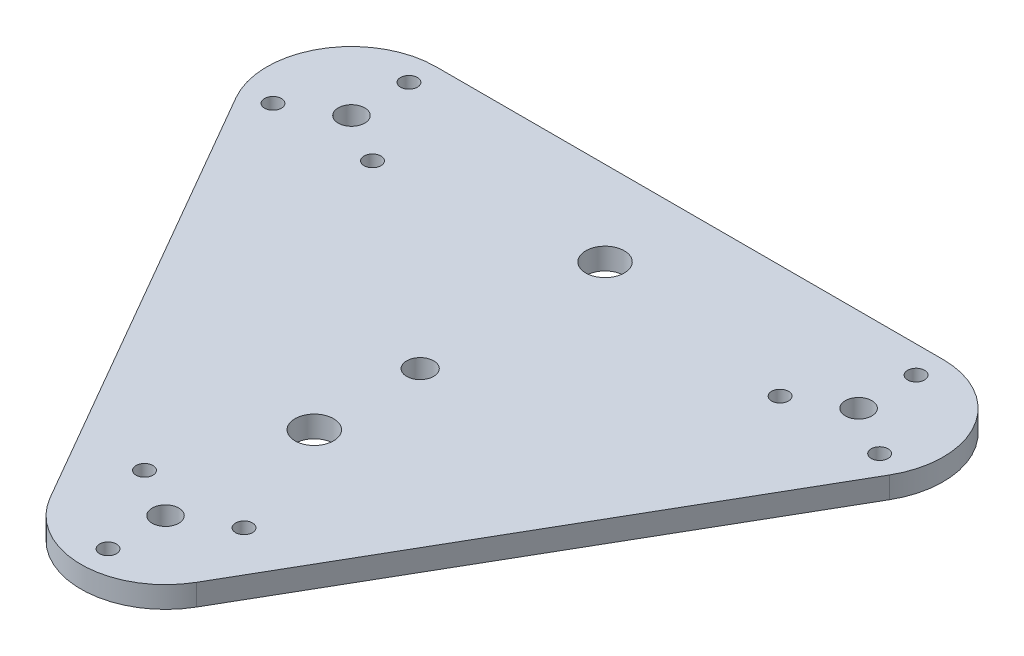
SolidWorks part; units mm, degrees
ref_plane "Plan de face" through (0, 0, 0) normal (0, 0, 1) x (1, 0, 0)
ref_plane "Plan de dessus" through (0, 0, 0) normal (0, 1, 0) x (1, 0, 0)
ref_plane "Plan de droite" through (0, 0, 0) normal (1, 0, 0) x (0, 0, -1)
sketch "Esquisse1" plane through (0, 0, 0) normal (0, 1, 0) x (1, 0, 0)
  line L0 (-96.6546, 52.5069) -> (-21.6546, -77.4931)
  line L1 (96.6546, 52.5069) -> (21.6546, -77.4931)
  line L2 (-75, 90) -> (75, 90)
  line L3 (75, 65) -> (-75, 65) construction
  arc A3 (-75, 90) -> (-96.6546, 52.5069) centre (-75, 65) ccw
  arc A4 (96.6546, 52.5069) -> (75, 90) centre (75, 65) ccw
  arc A5 (-21.6546, -77.4931) -> (21.6546, -77.4931) centre (0, -65) ccw
  circle A6 centre (0, 65) radius 5.7
  circle A7 centre (-75, 65) radius 3.925
  circle A8 centre (75, 65) radius 3.925
  circle A9 centre (0, -65) radius 3.925
  dimension "D1" = 11.4
  dimension "D6" = 50
  dimension "D7" = 7.85
  dimension "D2" = 65
  dimension "D3" = 65
  dimension "D4" = 150
  dimension "D5" = 75
extrude "Boss.-Extru.1" add sketch "Esquisse1" along normal blind 6.35
sketch "Esquisse4" plane through (0, 0, 0) normal (0, -1, 0) x (1, 0, 0)
  circle A0 centre (-75, -82) radius 2.5
  circle A1 centre (-89.7224, -56.5) radius 2.5
  circle A2 centre (-60.2776, -56.5) radius 2.5
  circle A3 centre (60.279, -56.4992) radius 2.5
  circle A4 centre (75.0015, -81.9992) radius 2.5
  circle A5 centre (89.7239, -56.4992) radius 2.5
  circle A6 centre (14.7224, 56.5) radius 2.5
  circle A7 centre (0, 82) radius 2.5
  circle A8 centre (-14.7224, 56.5) radius 2.5
extrude "Enlèv. mat.-Extru.1" cut sketch "Esquisse4" along a picked direction on the side against the normal blind 6.35
sketch "Esquisse5" plane through (0, 6.35, 0) normal (0, 1, 0) x (1, 0, 0)
  circle A0 centre (0.0008, 10.325) radius 4
  circle A1 centre (0.0008, 10.325) radius 4 construction
  circle A2 centre (0.0008, 10.325) radius 4 construction
extrude "Enlèv. mat.-Extru.2" cut sketch "Esquisse5" against normal through all
sketch "Esquisse6" plane through (0, 6.35, 0) normal (0, 1, 0) x (1, 0, 0)
  circle A0 centre (0, -21) radius 5.7
  circle A1 centre (0, 65) radius 5.7 construction
extrude "Enlèv. mat.-Extru.3" cut sketch "Esquisse6" against normal through all
sketch "Esquisse7" plane through (0, 6.35, 0) normal (0, 1, 0) x (1, 0, 0)
  line L0 (0, 65) -> (0.0008, 10.325) construction
